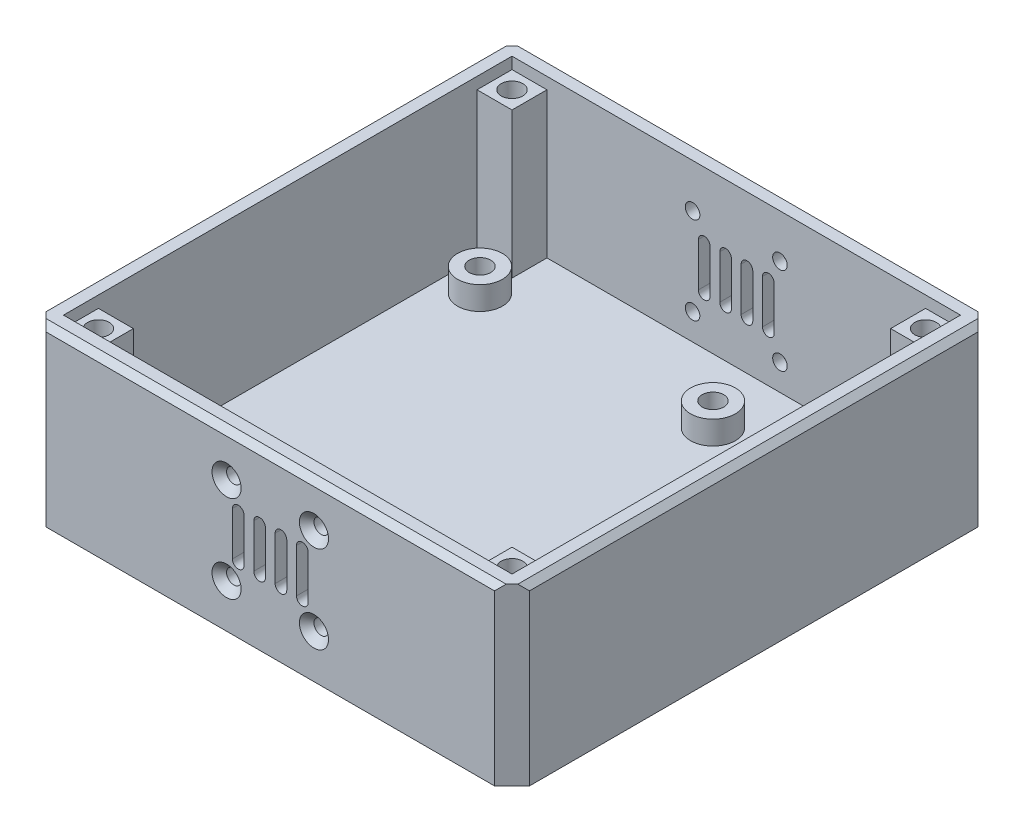
SolidWorks part; units mm, degrees
ref_plane "Front Plane" through (0, 0, 0) normal (0, 0, 1) x (1, 0, 0)
ref_plane "Top Plane" through (0, 0, 0) normal (0, 1, 0) x (1, 0, 0)
ref_plane "Right Plane" through (0, 0, 0) normal (1, 0, 0) x (0, 0, -1)
sketch "Sketch3" plane through (0, 0, 0) normal (0, 1, 0) x (1, 0, 0)
  line L1 (41.5, -41.5) -> (-41.5, -41.5)
  line L2 (41.5, -41.5) -> (41.5, 41.5)
  line L3 (41.5, 41.5) -> (-41.5, 41.5)
  line L4 (-41.5, -41.5) -> (-41.5, 41.5)
  line L5 (41.5, -41.5) -> (-41.5, 41.5) construction
  line L6 (41.5, 41.5) -> (-41.5, -41.5) construction
  point P0 (0, 0)
  dimension "D1" = 83
extrude "Body" add sketch "Sketch3" along normal mid plane 30
shell "Shell" thickness 3
sketch "Sketch4" plane through (0, -12, 0) normal (0, 1, 0) x (1, 0, 0)
  line L0 (-38.5, 38.5) -> (-32.5, 32.5) construction
  line L1 (-38.5, 38.5) -> (-32.5, 38.5)
  line L2 (-38.5, 38.5) -> (-38.5, 32.5)
  line L3 (-38.5, 32.5) -> (-32.5, 32.5)
  line L4 (-32.5, 38.5) -> (-32.5, 32.5)
  line L5 (0, -1000) -> (0, 49000) construction
  line L6 (-1000, 0) -> (49000, 0) construction
  line L7 (38.5, 38.5) -> (32.5, 32.5) construction
  line L8 (32.5, 38.5) -> (32.5, 32.5)
  line L9 (38.5, 32.5) -> (32.5, 32.5)
  line L10 (38.5, 38.5) -> (38.5, 32.5)
  line L11 (38.5, 38.5) -> (32.5, 38.5)
  line L12 (38.5, -38.5) -> (32.5, -32.5) construction
  line L13 (-38.5, -38.5) -> (-32.5, -32.5) construction
  line L14 (38.5, -38.5) -> (32.5, -38.5)
  line L15 (38.5, -38.5) -> (38.5, -32.5)
  line L16 (38.5, -32.5) -> (32.5, -32.5)
  line L17 (32.5, -38.5) -> (32.5, -32.5)
  line L18 (-32.5, -38.5) -> (-32.5, -32.5)
  line L19 (-38.5, -32.5) -> (-32.5, -32.5)
  line L20 (-38.5, -38.5) -> (-38.5, -32.5)
  line L21 (-38.5, -38.5) -> (-32.5, -38.5)
  circle A0 centre (-35.5, 35.5) radius 1.85
  circle A1 centre (35.5, 35.5) radius 1.85
  circle A2 centre (35.5, -35.5) radius 1.85
  circle A3 centre (-35.5, -35.5) radius 1.85
  dimension "D1" = 3.7
  dimension "D2" = 6
extrude "Inserts_Suppport" add sketch "Sketch4" along normal offset from surface (25 mm away) 2 up to face at (0, 15, 0)
chamfer "Chamfer1" distance 3 angle 45 4 edges at (-41.5, 0, 41.5) (-41.5, 0, -41.5) (41.5, 0, -41.5) (41.5, 0, 41.5)
chamfer "Chamfer2" distance 1 angle 45 4 edges at (0, 15, -41.5) (-41.5, 15, 0) (0, 15, 41.5) (41.5, 15, 0)
sketch "Sketch5" plane through (0, 0, 41.5) normal (0, 0, 1) x (1, 0, 0)
  line L0 (-5.5, 3.75) -> (-5.5, -3.75) construction
  line L1 (7.5, -7.5) -> (-7.5, -7.5) construction
  line L2 (7.5, -7.5) -> (7.5, 7.5) construction
  line L3 (7.5, 7.5) -> (-7.5, 7.5) construction
  line L4 (-7.5, -7.5) -> (-7.5, 7.5) construction
  line L5 (7.5, -7.5) -> (-7.5, 7.5) construction
  line L6 (7.5, 7.5) -> (-7.5, -7.5) construction
  line L7 (-4.5, 3.75) -> (-4.5, -3.75)
  line L8 (-6.5, 3.75) -> (-6.5, -3.75)
  line L9 (-1.8333, 3.75) -> (-1.8333, -3.75) construction
  line L10 (-0.8333, 3.75) -> (-0.8333, -3.75)
  line L11 (-2.8333, 3.75) -> (-2.8333, -3.75)
  line L12 (1.8333, 3.75) -> (1.8333, -3.75) construction
  line L13 (2.8333, 3.75) -> (2.8333, -3.75)
  line L14 (0.8333, 3.75) -> (0.8333, -3.75)
  line L15 (5.5, 3.75) -> (5.5, -3.75) construction
  line L16 (6.5, 3.75) -> (6.5, -3.75)
  line L17 (4.5, 3.75) -> (4.5, -3.75)
  circle A0 centre (-7.5, 7.5) radius 1.25
  circle A1 centre (-7.5, -7.5) radius 1.25
  circle A2 centre (7.5, -7.5) radius 1.25
  circle A3 centre (7.5, 7.5) radius 1.25
  arc A4 (-4.5, 3.75) -> (-6.5, 3.75) centre (-5.5, 3.75) ccw
  arc A5 (-6.5, -3.75) -> (-4.5, -3.75) centre (-5.5, -3.75) ccw
  arc A6 (-0.8333, 3.75) -> (-2.8333, 3.75) centre (-1.8333, 3.75) ccw
  arc A7 (-2.8333, -3.75) -> (-0.8333, -3.75) centre (-1.8333, -3.75) ccw
  arc A8 (2.8333, 3.75) -> (0.8333, 3.75) centre (1.8333, 3.75) ccw
  arc A9 (0.8333, -3.75) -> (2.8333, -3.75) centre (1.8333, -3.75) ccw
  arc A10 (6.5, 3.75) -> (4.5, 3.75) centre (5.5, 3.75) ccw
  arc A11 (4.5, -3.75) -> (6.5, -3.75) centre (5.5, -3.75) ccw
  point P0 (0, 0)
  point P12 (-5.5, 0)
  point P18 (11.9961, 0)
  point P20 (-1.8333, 0)
  point P27 (1.8333, 0)
  point P34 (5.5, 0)
  point P39 (-1.7422, 0)
  point P40 (1.8333, 0)
  point P41 (5.5, 0)
  point P42 (5.5, 5)
  point P43 (-4.5, -5)
  point P44 (-6.5, -5)
  point P45 (5.5, 0)
  point P46 (0, 0)
  point P47 (5.5, 5)
  point P48 (-1.8333, 0)
  dimension "D2" = 2.5
  dimension "D1" = 15
  dimension "D3" = 7.5
  dimension "D4" = 2
  dimension "D5" = 2
  dimension "D7" = 2
  dimension "D6" = 4
extrude "Air_Extraction" cut sketch "Sketch5" against normal through all
chamfer "Chamfer3" distance 1.25 angle 45 8 edges at (8.75, 7.5, 41.5) (8.75, -7.5, 41.5) (-6.25, -7.5, 41.5) (-6.25, 7.5, 41.5) (-6.25, 7.5, -41.5) (8.75, 7.5, -41.5) (8.75, -7.5, -41.5) (-6.25, -7.5, -41.5)
sketch "Sketch7" plane through (0, -12, 0) normal (0, 1, 0) x (1, 0, 0)
  line L0 (-13, 27.5) -> (-13, -27.5) construction
  line L1 (-33, 27.5) -> (7, 27.5) construction
  line L2 (-33, 27.5) -> (-33, -27.5) construction
  line L3 (-33, -27.5) -> (7, -27.5) construction
  line L4 (7, 27.5) -> (7, -27.5) construction
  line L5 (-33, 0) -> (7, 0) construction
  circle A0 centre (-33, 27.5) radius 1.85
  circle A1 centre (7, 27.5) radius 1.85
  circle A2 centre (7, -27.5) radius 1.85
  circle A3 centre (-33, -27.5) radius 1.85
  circle A4 centre (7, 27.5) radius 3.85
  circle A5 centre (-33, 27.5) radius 3.85
  circle A6 centre (-33, -27.5) radius 3.85
  circle A7 centre (7, -27.5) radius 3.85
  dimension "D4" = 3.7
  dimension "D1" = 40
  dimension "D2" = 55
  dimension "D3" = 13
  dimension "D5" = 2
extrude "Boss-Extrude1" add sketch "Sketch7" along normal blind 4
